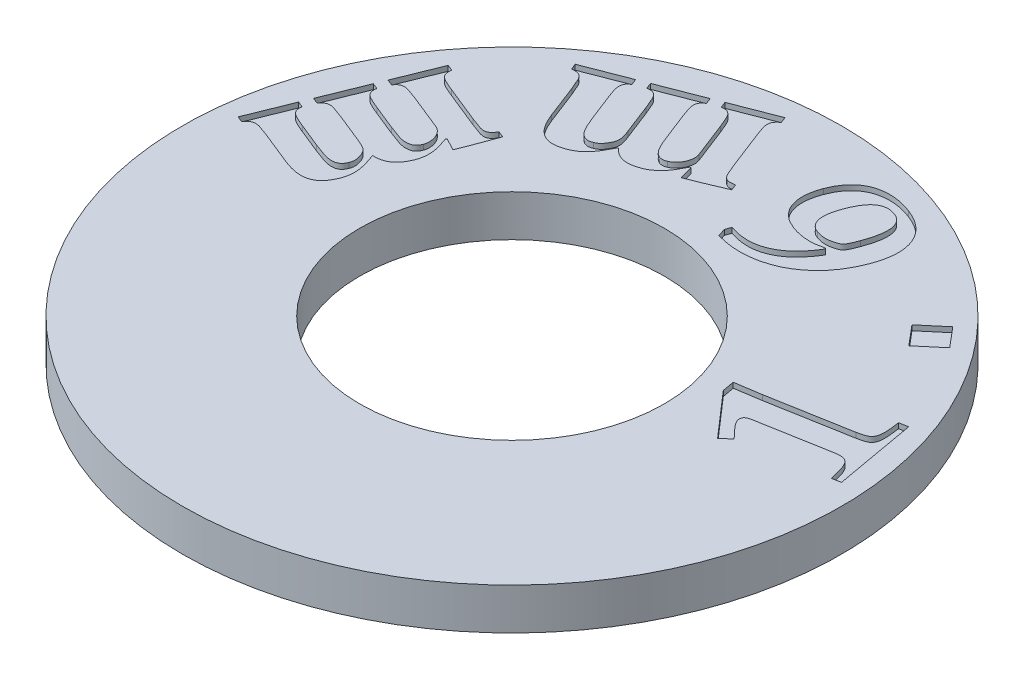
SolidWorks part; units mm, degrees
ref_plane "Front Plane" through (0, 0, 0) normal (0, 0, 1) x (1, 0, 0)
ref_plane "Top Plane" through (0, 0, 0) normal (0, 1, 0) x (1, 0, 0)
ref_plane "Right Plane" through (0, 0, 0) normal (1, 0, 0) x (0, 0, -1)
sketch "Sketch1" plane through (0, 0, 0) normal (0, 1, 0) x (1, 0, 0)
  circle A0 centre (0, 0) radius 12.7
  dimension "D1" = 25.4
extrude "Boss-Extrude1" add sketch "Sketch1" along normal blind 1.6
sketch "Sketch2" plane through (0, 0, 0) normal (0, -1, 0) x (-1, 0, 0)
  circle A0 centre (0, 0) radius 5.8674
  dimension "D1" = 11.7348
extrude "Cut-Extrude1" cut sketch "Sketch2" against normal through all
sketch "Sketch4" plane through (0, 1.6, 0) normal (0, 1, 0) x (1, 0, 0)
  circle A0 centre (0, 0) radius 12.0429 construction
  text T0 "<b>1.6mm</b>" font "Cambria" height 5.08
extrude "Cut-Extrude2" cut sketch "Sketch4" against normal blind 0.2
